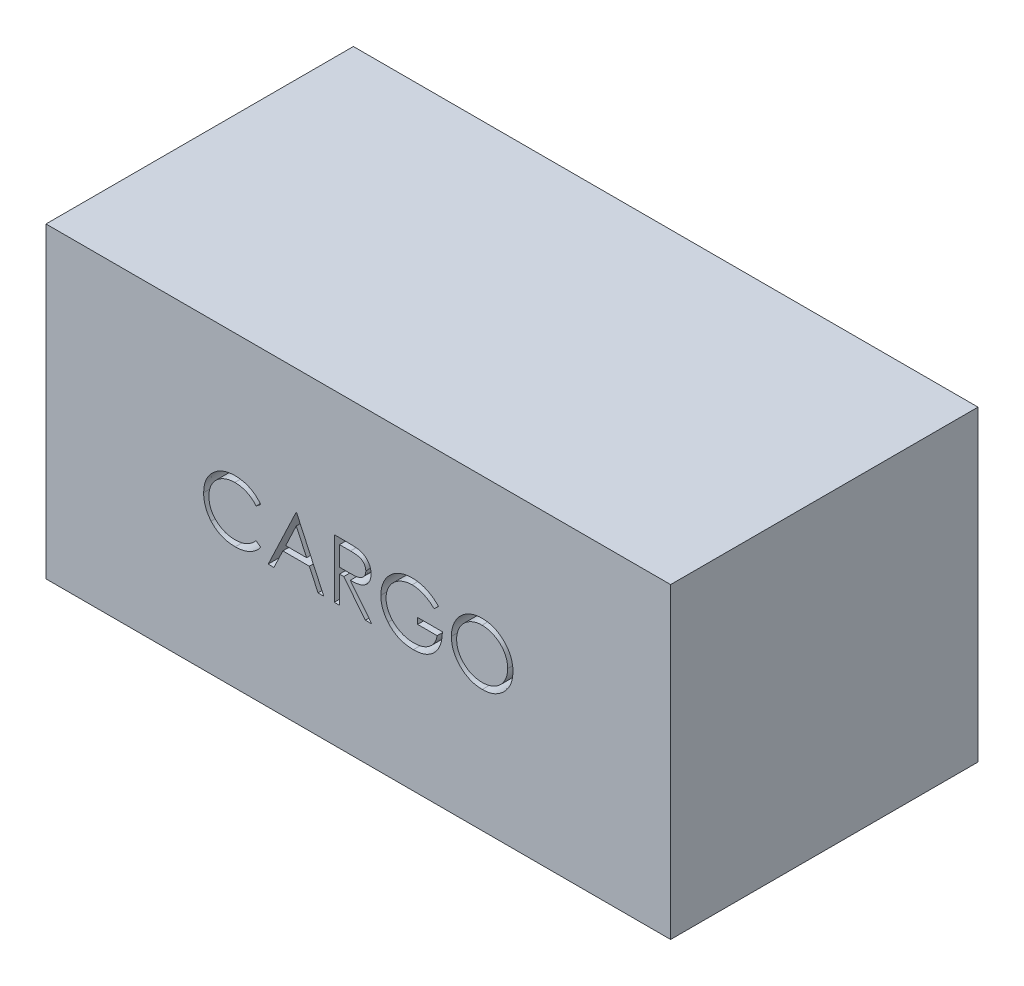
SolidWorks part; units mm, degrees
ref_plane "Front Plane" through (0, 0, 0) normal (0, 0, 1) x (1, 0, 0)
ref_plane "Top Plane" through (0, 0, 0) normal (0, 1, 0) x (1, 0, 0)
ref_plane "Right Plane" through (0, 0, 0) normal (1, 0, 0) x (0, 0, -1)
sketch "Sketch1" plane through (0, 0, 0) normal (0, 1, 0) x (1, 0, 0)
  line L1 (-69.0476, 30.7823) -> (134.1524, 30.7823)
  line L2 (-69.0476, 30.7823) -> (-69.0476, -69.2177)
  line L3 (-69.0476, -69.2177) -> (134.1524, -69.2177)
  line L4 (134.1524, 30.7823) -> (134.1524, -69.2177)
  dimension "D1" = 100
  dimension "D2" = 203.2
extrude "Boss-Extrude1" add sketch "Sketch1" along normal blind 100
sketch "Sketch2" plane through (0, 0, 69.2177) normal (0, 0, 1) x (1, 0, 0)
  text T0 "CARGO" font "Century Gothic" height in points 72
  point P1 (-20.9296, 35.7689)
  point P2 (-18.2839, 45.974)
  point P3 (-19.2288, 40.3045)
extrude "Cut-Extrude1" cut sketch "Sketch2" against normal blind 10
